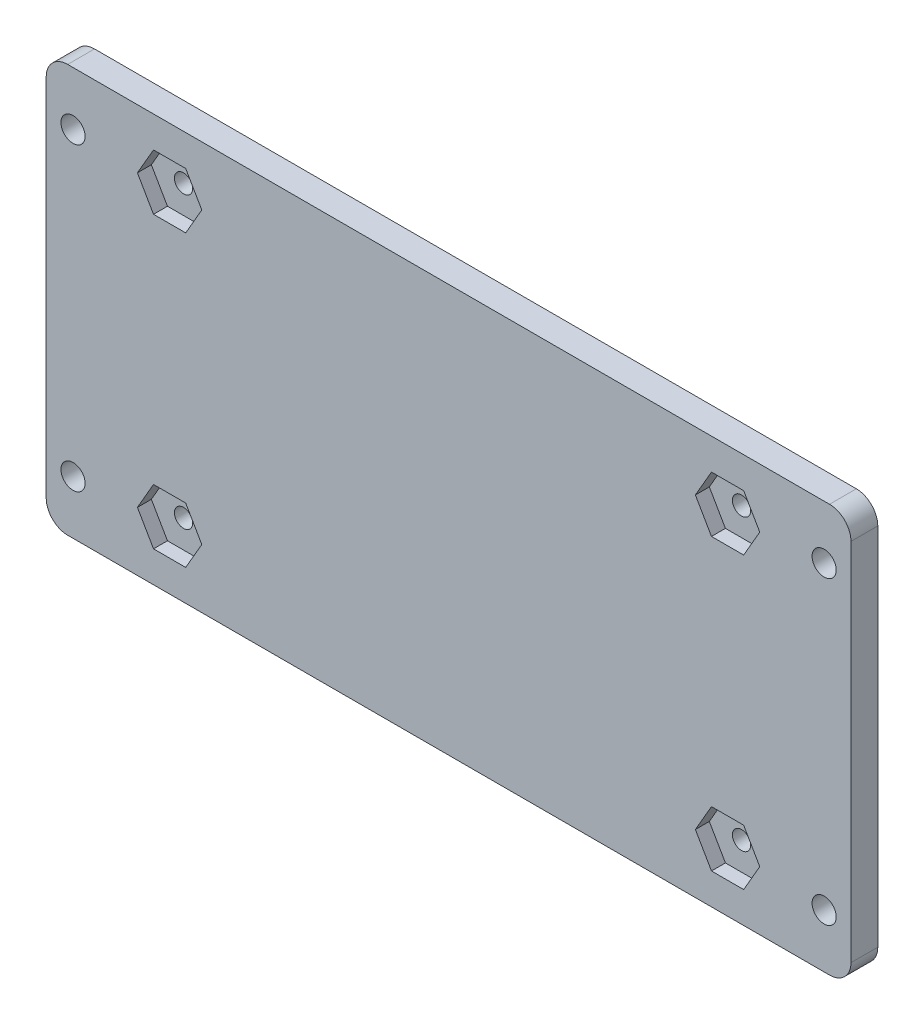
SolidWorks part; units mm, degrees
ref_plane "Front Plane" through (0, 0, 0) normal (0, 0, 1) x (1, 0, 0)
ref_plane "Top Plane" through (0, 0, 0) normal (0, 1, 0) x (1, 0, 0)
ref_plane "Right Plane" through (0, 0, 0) normal (1, 0, 0) x (0, 0, -1)
sketch "Sketch1" plane through (0, 0, 0) normal (0, 0, 1) x (1, 0, 0)
  line L1 (-75, 38) -> (75, 38)
  line L2 (-75, 38) -> (-75, -38)
  line L3 (-75, -38) -> (75, -38)
  line L4 (75, 38) -> (75, -38)
  point P4 (0, 38)
  point P6 (-75, 0)
  dimension "D1" = 150
  dimension "D2" = 76
extrude "Boss-Extrude1" add sketch "Sketch1" along normal blind 5
fillet "Fillet1" radius 4 4 edges at (75, -38, 2.5) (-75, -38, 2.5) (-75, 38, 2.5) (75, 38, 2.5)
sketch "Sketch2" plane through (0, 0, 0) normal (0, 0, -1) x (-1, 0, 0)
  line L0 (2.75, 0) -> (-2.75, 0) construction
  line L1 (0, 2.75) -> (0, -2.75) construction
  circle A0 centre (52, -27) radius 1.7
  circle A1 centre (52, 27) radius 1.7
  circle A2 centre (-52, 27) radius 1.7
  circle A3 centre (-52, -27) radius 1.7
  dimension "D1" = 3.4
  dimension "D2" = 52
  dimension "D3" = 27
extrude "Cut-Extrude1" cut sketch "Sketch2" against normal through all
sketch "Sketch3" plane through (0, 0, 5) normal (0, 0, 1) x (1, 0, 0)
  line L0 (0, -2.75) -> (0, 2.75) construction
  line L1 (-49, 21.8038) -> (-46, 27)
  line L2 (-46, 27) -> (-49, 32.1962)
  line L3 (-49, 32.1962) -> (-55, 32.1962)
  line L4 (-55, 32.1962) -> (-58, 27)
  line L5 (-58, 27) -> (-55, 21.8038)
  line L6 (-55, 21.8038) -> (-49, 21.8038)
  line L7 (55, 21.8038) -> (49, 21.8038)
  line L8 (58, 27) -> (55, 21.8038)
  line L9 (55, 32.1962) -> (58, 27)
  line L10 (49, 32.1962) -> (55, 32.1962)
  line L11 (46, 27) -> (49, 32.1962)
  line L12 (49, 21.8038) -> (46, 27)
  line L13 (2.75, 0) -> (-2.75, 0) construction
  line L14 (49, -21.8038) -> (46, -27)
  line L15 (46, -27) -> (49, -32.1962)
  line L16 (49, -32.1962) -> (55, -32.1962)
  line L17 (55, -32.1962) -> (58, -27)
  line L18 (58, -27) -> (55, -21.8038)
  line L19 (55, -21.8038) -> (49, -21.8038)
  line L20 (-55, -21.8038) -> (-49, -21.8038)
  line L21 (-58, -27) -> (-55, -21.8038)
  line L22 (-55, -32.1962) -> (-58, -27)
  line L23 (-49, -32.1962) -> (-55, -32.1962)
  line L24 (-46, -27) -> (-49, -32.1962)
  line L25 (-49, -21.8038) -> (-46, -27)
  circle A0 centre (-52, 27) radius 5.1962 construction
  circle A1 centre (52, 27) radius 5.1962 construction
  circle A2 centre (52, -27) radius 5.1962 construction
  circle A3 centre (-52, -27) radius 5.1962 construction
  dimension "D1" = 6
extrude "Cut-Extrude2" cut sketch "Sketch3" against normal blind 2.6
sketch "Sketch4" plane through (0, 0, 5) normal (0, 0, 1) x (1, 0, 0)
  line L0 (0, -2.75) -> (0, 2.75) construction
  line L1 (2.75, 0) -> (-2.75, 0) construction
  circle A0 centre (-70, 28) radius 2.25
  circle A1 centre (70, 28) radius 2.25
  circle A2 centre (70, -28) radius 2.25
  circle A3 centre (-70, -28) radius 2.25
  dimension "D2" = 4.5
  dimension "D1" = 70
  dimension "D3" = 28
extrude "Cut-Extrude3" cut sketch "Sketch4" against normal through all and the other way through all
